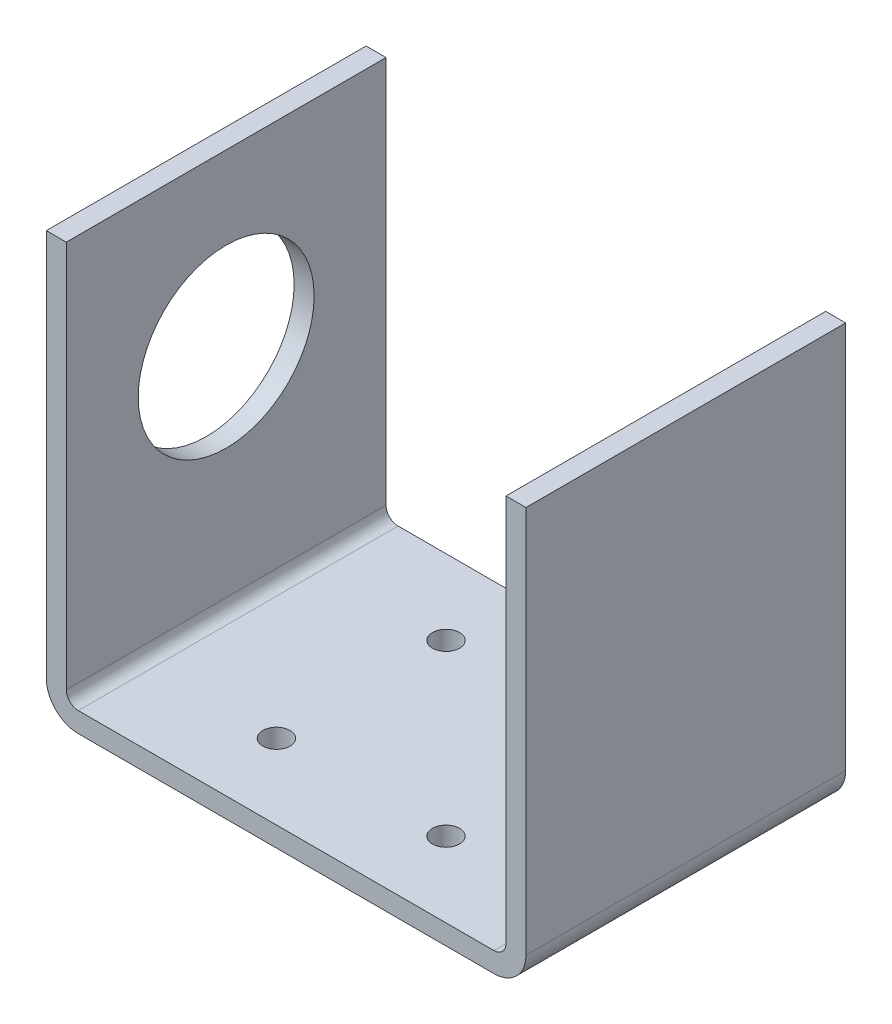
SolidWorks part; units mm, degrees
ref_plane "Front Plane" through (0, 0, 0) normal (0, 0, 1) x (1, 0, 0)
ref_plane "Top Plane" through (0, 0, 0) normal (0, 1, 0) x (1, 0, 0)
ref_plane "Right Plane" through (0, 0, 0) normal (1, 0, 0) x (0, 0, -1)
sketch "Sketch1" plane through (0, 0, 0) normal (0, 1, 0) x (1, 0, 0)
  line L1 (-30, -20) -> (30, -20)
  line L2 (-30, -20) -> (-30, 20)
  line L3 (-30, 20) -> (30, 20)
  line L4 (30, -20) -> (30, 20)
  line L5 (-30, -20) -> (30, 20) construction
  line L6 (-30, 20) -> (30, -20) construction
  circle A0 centre (0, 0) radius 15 construction
  dimension "D1" = 30
  dimension "D2" = 40
  dimension "D3" = 60
extrude "Boss-Extrude1" add sketch "Sketch1" along normal blind 2.5
hole_wizard "M3 Clearance Hole1" positions "Sketch2" profile "Sketch3" hole size "M3" standard "DIN" end condition through all
sketch "Sketch2" plane through (0, 2.5, 0) normal (0, 1, 0) x (1, 0, 0)
  line L0 (0, 0) -> (10.6066, 10.6066) construction
  circle A0 centre (0, 0) radius 15 construction
  point P7 (10.6066, 10.6066)
  point P15 (10.6066, -10.6066)
  point P16 (-10.6066, -10.6066)
  point P17 (-10.6066, 10.6066)
  dimension "D1" = 30
  dimension "D2" = 4
sketch "Sketch3" plane through (-10.6066, 2.5, -10.6066) normal (1, 0, 0) x (0, 0, 1)
  line L0 (0, 0) -> (0, 2.5)
  line L1 (0, 2.5) -> (1.7, 2.5)
  line L2 (1.7, 2.5) -> (1.7, 0)
  line L5 (1.7, 0) -> (0, 0)
  line L11 (0, -6.35) -> (0, 107.95) construction
  dimension "Thru Hole Dia." = 3.4
  dimension "Thru Hole Depth" = 2.5
sketch "Sketch4" plane through (0, 0, 20) normal (0, 0, 1) x (1, 0, 0)
  line L0 (-30, 2.5) -> (-30, 52.5)
  line L1 (-30, 52.5) -> (-27.5, 52.5)
  line L2 (-27.5, 52.5) -> (-27.5, 2.5)
  line L3 (-30, 2.5) -> (30, 2.5) construction
  line L4 (-27.5, 2.5) -> (-30, 2.5)
  line L5 (0, 0) -> (0, 16.072) construction
  line L6 (27.5, 52.5) -> (27.5, 2.5)
  line L7 (30, 52.5) -> (27.5, 52.5)
  line L8 (30, 2.5) -> (30, 52.5)
  line L9 (27.5, 2.5) -> (30, 2.5)
  dimension "D1" = 2.5
  dimension "D2" = 50
extrude "Boss-Extrude2" add sketch "Sketch4" against normal up to surface (40 mm away) up to face at (0, 1.25, -20)
fillet "Fillet1" radius 4 2 edges at (30, 0, 0) (-30, 0, 0)
fillet "Fillet2" radius 1.5 2 edges at (-27.5, 2.5, 0) (27.5, 2.5, 0)
sketch "Sketch6" plane through (-30, 0, 0) normal (-1, 0, 0) x (0, 0, 1)
  line L0 (0, 52.5) -> (0, 31.1749) construction
  line L1 (-20, 52.5) -> (20, 52.5) construction
  circle A0 centre (0, 31.1749) radius 11
  dimension "D1" = 22
extrude "Cut-Extrude1" cut sketch "Sketch6" against normal up to next and the other way through all
